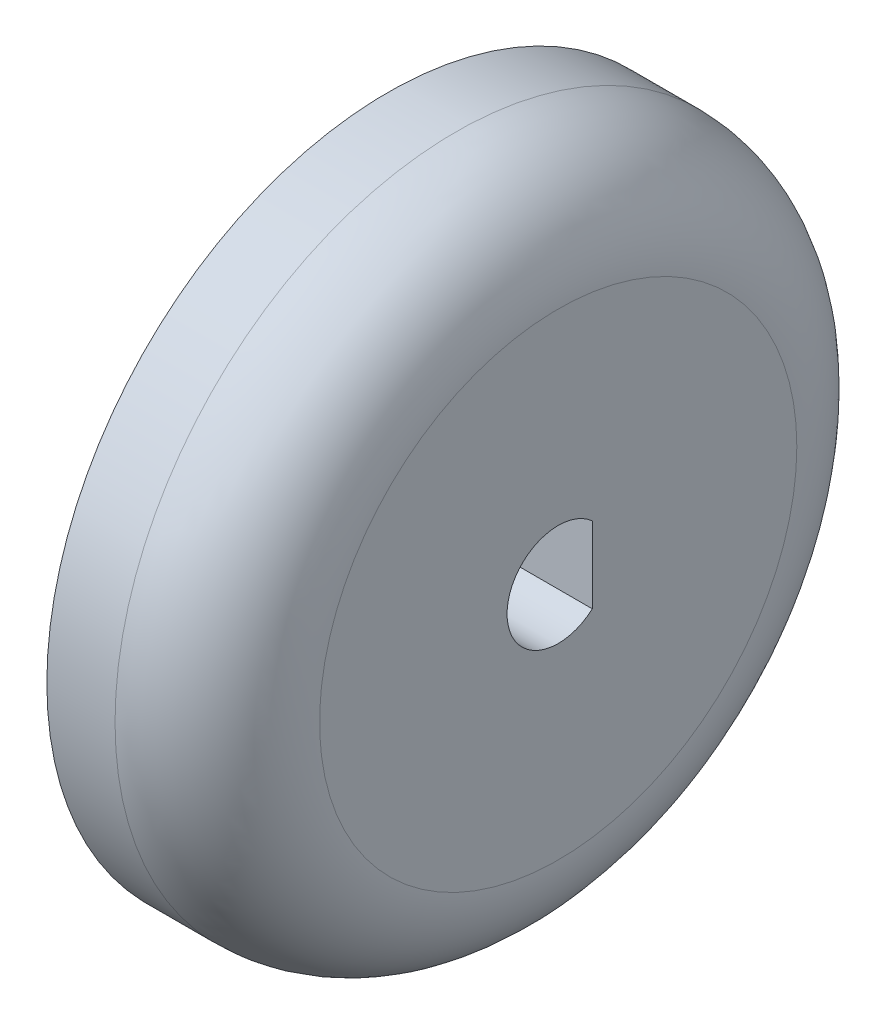
SolidWorks part; units mm, degrees
ref_plane "Front" through (0, 0, 0) normal (0, 0, 1) x (1, 0, 0)
ref_plane "Top" through (0, 0, 0) normal (0, 1, 0) x (1, 0, 0)
ref_plane "Right" through (0, 0, 0) normal (1, 0, 0) x (0, 0, -1)
sketch "Sketch1" plane through (0, 0, 0) normal (1, 0, 0) x (0, -1, 0)
  circle A0 centre (0, 0) radius 10
  dimension "D1" = 20
extrude "Boss-Extrude1" add sketch "Sketch1" along normal blind 10
sketch "Sketch2" plane through (10, 0, 0) normal (1, 0, 0) x (0, -1, 0)
  line L0 (-1.118, 1) -> (1.118, 1)
  arc A0 (-1.118, 1) -> (1.118, 1) centre (0, 0) ccw
  circle A1 centre (0, 0) radius 10 construction
  dimension "D1" = 1
  dimension "D2" = 1.5
extrude "Cut-Extrude1" cut sketch "Sketch2" against normal through all
fillet "Fillet1" radius 3 2 edges at (0, 0, -10) (10, 0, -10)
ref_plane "Plane1" through (5, 0, 0) normal (-1, 0, 0) x (0, 0, 1)
other "SurfaceCut1"
